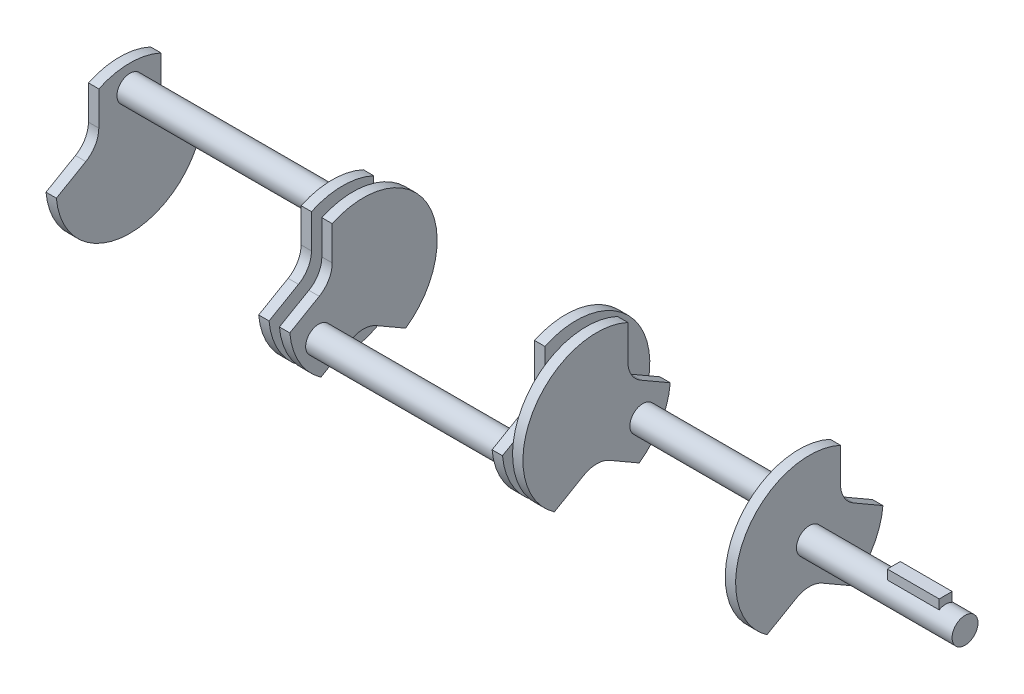
SolidWorks part; units mm, degrees
ref_plane "Front Plane" through (0, 0, 0) normal (0, 0, 1) x (1, 0, 0)
ref_plane "Top Plane" through (0, 0, 0) normal (0, 1, 0) x (1, 0, 0)
ref_plane "Right Plane" through (0, 0, 0) normal (1, 0, 0) x (0, 0, -1)
sketch "Sketch5" plane through (0, 0, 0) normal (1, 0, 0) x (0, 0, -1)
  line L0 (0, 85.6929) -> (0, -94.6727) construction
  line L2 (15.24, 32.778) -> (15.24, 16.1312)
  line L4 (-15.24, 32.778) -> (-15.24, 16.1312)
  line L8 (36.0066, -3.1908) -> (21.59, 5.1326)
  line L11 (-36.0066, -3.1908) -> (-21.59, 5.1326)
  line L26 (-20.7666, -29.5872) -> (-6.35, -21.2638) [skipped]
  line L27 (20.7666, -29.5872) -> (6.35, -21.2638) [skipped]
  arc A0 (-36.0066, -3.1908) -> (36.0066, -3.1908) centre (0, 0) ccw
  arc A1 (-15.24, 16.1312) -> (-21.59, 5.1326) centre (-27.94, 16.1312) cw
  arc A3 (15.24, 16.1312) -> (21.59, 5.1326) centre (27.94, 16.1312) ccw
  arc A4 (15.24, 32.778) -> (-15.24, 32.778) centre (0, 0) ccw
  point P7 (0, 25.4)
  point P21 (0, -17.5976)
  point P24 (0, 0)
  dimension "D4" = 12.7
  dimension "D3" = 3
extrude "Boss-Extrude2" add sketch "Sketch5" along normal blind 5.08
move or copy body "Body-Move/Copy11" bodies to move or copy 103 copy yes number of copies 1 translate (104.14, 0, 0)
move or copy body "Body-Move/Copy12" bodies to move or copy 113 copy yes number of copies 1 translate (10.16, 0, 0)
move or copy body "Body-Move/Copy13" bodies to move or copy 114 copy no rotation origin (0, 0, 0) rotation axis (1, 0, 0) rotation angle 120
move or copy body "Body-Move/Copy14" bodies to move or copy 115 copy yes number of copies 1 translate (104.14, 0, 0)
sketch "Sketch8" plane through (5.08, 0, 0) normal (1, 0, 0) x (0, 0, -1)
  circle A0 centre (0, 25.4) radius 6.35
  dimension "D1" = 25.4
sketch "Sketch9" plane through (109.22, 0, 0) normal (1, 0, 0) x (0, 0, -1)
  circle A0 centre (0, 0) radius 12.7
  dimension "D1" = 25.4
sketch "Sketch11" plane through (119.38, 0, 0) normal (1, 0, 0) x (0, 0, -1)
  circle A0 centre (-21.89, -12.8837) radius 6.35
  dimension "D1" = 25.4
move or copy body "Body-Move/Copy16" bodies to move or copy 116 copy yes number of copies 1 translate (10.16, 0, 0)
move or copy body "Body-Move/Copy18" bodies to move or copy 124 copy no rotation origin (0, 0, 0) rotation axis (1, 0, 0) rotation angle 120
move or copy body "Body-Move/Copy19" bodies to move or copy 126 copy yes number of copies 1 translate (104.14, 0, 0)
extrude "Boss-Extrude3" add sketch "Sketch8" along normal up to surface (99.06 mm away) contours A0
extrude "Boss-Extrude4" add sketch "Sketch9" along normal up to surface (5.08 mm away)
extrude "Boss-Extrude5" add sketch "Sketch11" along normal up to surface (99.06 mm away)
sketch "Sketch12" plane through (223.52, 0, 0) normal (1, 0, 0) x (0, 0, -1)
  circle A0 centre (0, 0) radius 12.7
sketch "Sketch13" plane through (233.68, 0, 0) normal (1, 0, 0) x (0, 0, -1)
  circle A0 centre (22.5749, -11.6418) radius 6.35
  arc A1 (20.7666, -29.5872) -> (36.0066, -3.1908) centre (0, 0) ccw construction
  point P7 (31.3048, -18.0739)
  dimension "D1" = 25.4
extrude "Boss-Extrude6" add sketch "Sketch13" along normal up to surface (99.06 mm away)
sketch "Sketch14" plane through (337.82, 0, 0) normal (1, 0, 0) x (0, 0, -1)
  circle A0 centre (0, 0) radius 6.35
extrude "Boss-Extrude7" add sketch "Sketch14" along normal blind 76.2
ref_plane "Plane1" through (0, 10.16, 0) normal (0, 1, 0) x (1, 0, 0)
sketch "Sketch15" plane through (0, 10.16, 0) normal (0, 1, 0) x (1, 0, 0)
  line L0 (404.5438, 3.175) -> (404.5438, -3.175)
  line L1 (404.5438, -3.175) -> (379.1438, -3.175)
  line L2 (404.5438, 3.175) -> (379.1438, 3.175)
  line L3 (379.1438, 3.175) -> (379.1438, -3.175)
  line L4 (343.1319, 0) -> (420.8592, 0) construction
  point P7 (404.5438, 0)
  point P8 (379.1438, 0)
  dimension "D1" = 6.35
  dimension "D2" = 25.4
extrude "Boss-Extrude8" add sketch "Sketch15" against normal up to surface (4.6607 mm away)
